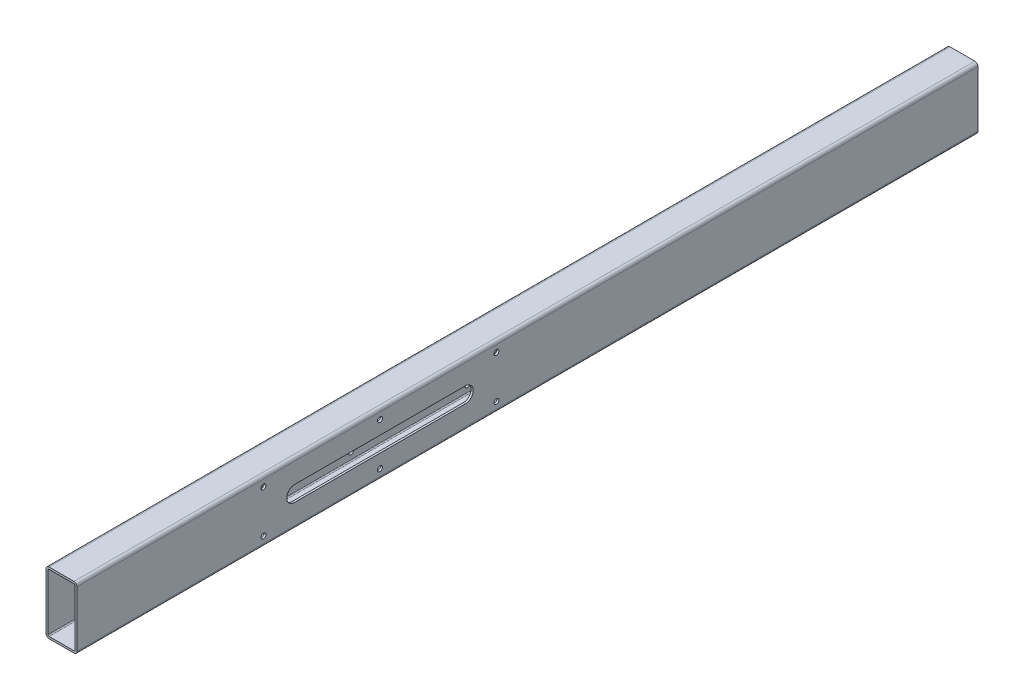
SolidWorks part; units mm, degrees
material "6061-T6 (SS)"
ref_plane "Front Plane" through (0, 0, 0) normal (0, 0, 1) x (1, 0, 0)
ref_plane "Top Plane" through (0, 0, 0) normal (0, 1, 0) x (1, 0, 0)
ref_plane "Right Plane" through (0, 0, 0) normal (1, 0, 0) x (0, 0, -1)
sketch "Sketch1" plane through (0, 0, 0) normal (0, 0, 1) x (1, 0, 0)
  line L1 (10.16, -25.4) -> (-10.16, -25.4)
  line L2 (12.7, -22.86) -> (12.7, 22.86)
  line L3 (10.16, 25.4) -> (-10.16, 25.4)
  line L4 (-12.7, -22.86) -> (-12.7, 22.86)
  line L5 (12.7, -25.4) -> (-12.7, 25.4) construction
  line L6 (12.7, 25.4) -> (-12.7, -25.4) construction
  arc A0 (-10.16, -25.4) -> (-12.7, -22.86) centre (-10.16, -22.86) cw
  arc A1 (10.16, -25.4) -> (12.7, -22.86) centre (10.16, -22.86) ccw
  arc A2 (12.7, 22.86) -> (10.16, 25.4) centre (10.16, 22.86) ccw
  arc A3 (-10.16, 25.4) -> (-12.7, 22.86) centre (-10.16, 22.86) ccw
  point P0 (0, 0)
  dimension "D3" = 2.54
  dimension "D1" = 25.4
  dimension "D2" = 50.8
extrude "Extrude-Thin1" add sketch "Sketch1" along normal blind 736.6 thin
sketch "Sketch2" [suppressed] plane through (-12.7, 0, 0) normal (-1, 0, 0) x (0, 0, 1)
  line L0 (25.4, 0) -> (152.4, 0) construction
  line L1 (25.4, 6.35) -> (152.4, 6.35)
  line L2 (25.4, -6.35) -> (152.4, -6.35)
  line L3 (0, 22.86) -> (0, -22.86) construction
  arc A0 (25.4, 6.35) -> (25.4, -6.35) centre (25.4, 0) ccw
  arc A1 (152.4, -6.35) -> (152.4, 6.35) centre (152.4, 0) ccw
  point P3 (88.9, 0)
  dimension "D1" = 12.7
  dimension "D2" = 127
  dimension "D3" = 25.4
extrude "Cut-Extrude1" [suppressed] cut sketch "Sketch2" against normal through all
sketch "Sketch3" plane through (-12.7, 0, 0) normal (-1, 0, 0) x (0, 0, 1)
  line L0 (558.8, 0) -> (419.1, 0) construction
  line L1 (558.8, -6.35) -> (419.1, -6.35)
  line L2 (558.8, 6.35) -> (419.1, 6.35)
  line L3 (736.6, 22.86) -> (736.6, -22.86) construction
  arc A0 (558.8, -6.35) -> (558.8, 6.35) centre (558.8, 0) ccw
  arc A1 (419.1, 6.35) -> (419.1, -6.35) centre (419.1, 0) ccw
  point P3 (488.95, 0)
  dimension "D1" = 12.7
  dimension "D2" = 177.8
  dimension "D3" = 139.7
extrude "Cut-Extrude2" cut sketch "Sketch3" against normal through all
sketch "Sketch5" plane through (12.7, 0, 0) normal (1, 0, 0) x (0, 0, -1)
  circle A0 centre (-393.7, 17.399) radius 2.0193 construction
  circle A1 centre (-393.7, -17.399) radius 2.0193 construction
  circle A2 centre (-488.95, 17.399) radius 2.0193 construction
  circle A3 centre (-488.95, -17.399) radius 2.0193 construction
  circle A4 centre (-584.2, -17.399) radius 2.0193 construction
  circle A5 centre (-584.2, 17.399) radius 2.0193 construction
  circle A6 centre (-393.7, 17.399) radius 2.0193
  circle A7 centre (-393.7, -17.399) radius 2.0193
  circle A8 centre (-488.95, 17.399) radius 2.0193
  circle A9 centre (-488.95, -17.399) radius 2.0193
  circle A10 centre (-584.2, -17.399) radius 2.0193
  circle A11 centre (-584.2, 17.399) radius 2.0193
extrude "Cut-Extrude3" cut sketch "Sketch5" against normal through all
